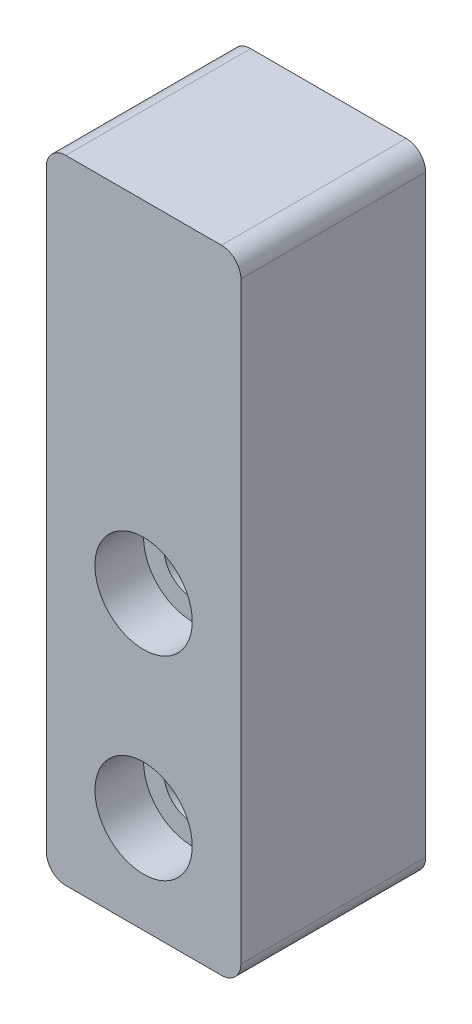
SolidWorks part; units mm, degrees
ref_plane "Front Plane" through (0, 0, 0) normal (0, 0, 1) x (1, 0, 0)
ref_plane "Top Plane" through (0, 0, 0) normal (0, 1, 0) x (1, 0, 0)
ref_plane "Right Plane" through (0, 0, 0) normal (1, 0, 0) x (0, 0, -1)
sketch "Sketch1" plane through (0, 0, 0) normal (0, 0, 1) x (1, 0, 0)
  line L1 (-10, 32.5) -> (10, 32.5)
  line L2 (-10, 32.5) -> (-10, -32.5)
  line L3 (-10, -32.5) -> (10, -32.5)
  line L4 (10, 32.5) -> (10, -32.5)
  line L5 (-10, 32.5) -> (10, -32.5) construction
  line L6 (-10, -32.5) -> (10, 32.5) construction
  point P0 (0, 0)
  dimension "D1" = 20
  dimension "D2" = 65
extrude "Boss-Extrude1" add sketch "Sketch1" along normal blind 19
hole_wizard "CBORE for M5 SHCS1" positions "Sketch2" profile "Sketch3" counterbore size "M5" standard "ANSI Metric" end condition through all
sketch "Sketch2" plane through (0, 0, 19) normal (0, 0, 1) x (1, 0, 0)
  line L1 (-10, -32.5) -> (10, -32.5) construction
  point P0 (0, -2.5)
  point P4 (0, -22.5)
  point P7 (0, 0)
  point P9 (0, 0)
  point P10 (0, -26.2806)
  dimension "D2" = 20
  dimension "D3" = 10
sketch "Sketch3" plane through (0, -2.5, 19) normal (1, 0, 0) x (0, -1, 0)
  line L0 (0, 0) -> (0, 19)
  line L1 (0, 19) -> (2.9, 19)
  line L3 (2.9, 19) -> (2.9, 5)
  line L4 (2.9, 5) -> (5, 5)
  line L5 (5, 5) -> (5, 0)
  line L7 (5, 0) -> (0, 0)
  line L11 (0, -6.35) -> (0, 107.95) construction
  dimension "Thru Hole Dia." = 5.8
  dimension "Thru Hole Depth" = 19
  dimension "C'Bore Dia." = 10
  dimension "C'Bore Depth" = 5
fillet "Fillet1" radius 2 4 edges at (10, -32.5, 9.5) (-10, -32.5, 9.5) (-10, 32.5, 9.5) (10, 32.5, 9.5)
